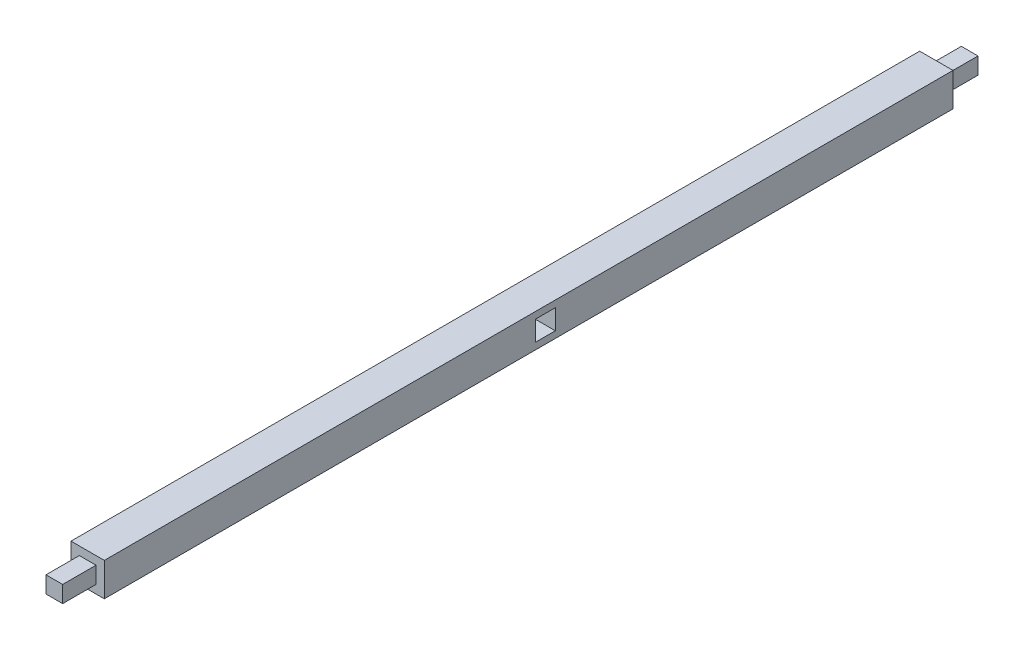
SolidWorks part; units mm, degrees
ref_plane "Front Plane" through (0, 0, 0) normal (0, 0, 1) x (1, 0, 0)
ref_plane "Top Plane" through (0, 0, 0) normal (0, 1, 0) x (1, 0, 0)
ref_plane "Right Plane" through (0, 0, 0) normal (1, 0, 0) x (0, 0, -1)
sketch "Sketch1" plane through (0, 0, 0) normal (0, 0, 1) x (1, 0, 0)
  line L1 (0, 0) -> (5, 0)
  line L2 (0, 0) -> (0, 5)
  line L3 (0, 5) -> (5, 5)
  line L4 (5, 0) -> (5, 5)
  dimension "D1" = 5
  dimension "D2" = 5
extrude "Boss-Extrude1" add sketch "Sketch1" along normal blind 127.3
sketch "Sketch2" plane through (0, 0, 0) normal (0, 0, -1) x (-1, 0, 0)
  line L0 (-5, 0) -> (-5, 5) construction
  line L1 (-3.75, 1.25) -> (-1.25, 1.25)
  line L2 (-3.75, 1.25) -> (-3.75, 3.75)
  line L3 (-3.75, 3.75) -> (-1.25, 3.75)
  line L4 (-1.25, 1.25) -> (-1.25, 3.75)
  line L5 (-5, 5) -> (0, 5) construction
  dimension "D1" = 2.5
  dimension "D2" = 2.5
  dimension "D3" = 1.25
  dimension "D4" = 1.25
extrude "Boss-Extrude2" add sketch "Sketch2" along normal blind 5
sketch "Sketch3" plane through (0, 0, 127.3) normal (0, 0, 1) x (1, 0, 0)
  line L0 (0, 5) -> (0, 0) construction
  line L1 (1.25, 1.25) -> (3.75, 1.25)
  line L2 (1.25, 1.25) -> (1.25, 3.75)
  line L3 (1.25, 3.75) -> (3.75, 3.75)
  line L4 (3.75, 1.25) -> (3.75, 3.75)
  line L5 (5, 5) -> (0, 5) construction
  dimension "D1" = 2.5
  dimension "D2" = 2.5
  dimension "D3" = 1.25
  dimension "D4" = 1.25
extrude "Boss-Extrude3" add sketch "Sketch3" along normal blind 5
sketch "Sketch4" plane through (0, 0, 0) normal (-1, 0, 0) x (0, 0, 1)
  line L0 (127.3, 5) -> (0, 5) construction
  line L1 (59.65, 1) -> (62.65, 1)
  line L2 (59.65, 1) -> (59.65, 4)
  line L3 (59.65, 4) -> (62.65, 4)
  line L4 (62.65, 1) -> (62.65, 4)
  line L5 (127.3, 5) -> (127.3, 0) construction
  dimension "D1" = 3
  dimension "D2" = 3
  dimension "D3" = 1
  dimension "D4" = 64.65
extrude "Cut-Extrude1" cut sketch "Sketch4" against normal blind 30
